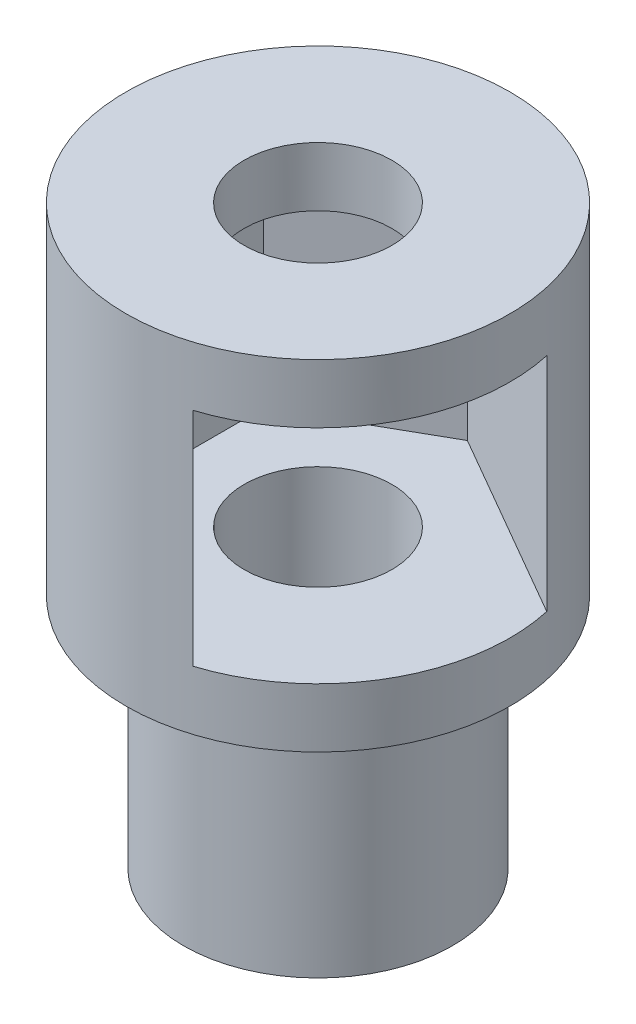
SolidWorks part; units mm, degrees
ref_plane "Front Plane" through (0, 0, 0) normal (0, 0, 1) x (1, 0, 0)
ref_plane "Top Plane" through (0, 0, 0) normal (0, 1, 0) x (1, 0, 0)
ref_plane "Right Plane" through (0, 0, 0) normal (1, 0, 0) x (0, 0, -1)
sketch "Sketch1" plane through (0, 0, 0) normal (0, 1, 0) x (1, 0, 0)
  circle A0 centre (0, 0) radius 4.55
  dimension "D1" = 9.1
extrude "Boss-Extrude1" add sketch "Sketch1" along normal blind 8 contours A0
sketch "Sketch2" plane through (0, 8, 0) normal (0, 1, 0) x (1, 0, 0)
  circle A0 centre (0, 0) radius 2.5
extrude "Cut-Extrude1" cut sketch "Sketch2" against normal blind 8
sketch "Sketch3" plane through (0, 8, 0) normal (0, 1, 0) x (1, 0, 0)
  circle A0 centre (0, 0) radius 6.5
  dimension "D1" = 13
extrude "Boss-Extrude4" add sketch "Sketch3" along normal blind 9.5 contours A0
sketch "Sketch5" plane through (0, 17.5, 0) normal (0, 1, 0) x (1, 0, 0)
  line L0 (0, 0) -> (4.3938, 0) construction
  line L3 (4.3938, 2.521) -> (4.3938, -2.521) construction
  line L5 (4.3938, -2.521) -> (-0.0062, -5.0614) construction
  line L9 (-0.0062, -5.0614) -> (-4.4062, -2.521) construction
  line L12 (-4.4062, -2.521) -> (-4.4062, 2.5597)
  line L13 (-4.4062, 2.5597) -> (-0.0062, 5.0614)
  line L14 (-0.0062, 5.0614) -> (4.3938, 2.521) construction
  line L15 (-4.1854, -2.6484) -> (43297.0847, -25002.6484) construction
  line L16 (0.0916, 5.0049) -> (43301.3618, -24994.9951) construction
  line L17 (7.8193, 0.5434) -> (3.436, -7.0487)
  line L18 (-0.0062, 5.0614) -> (7.8193, 0.5434)
  line L19 (3.436, -7.0487) -> (-4.4062, -2.521)
  circle A0 centre (0, 0) radius 6.5 construction
  point P6 (4.3938, 0)
  dimension "D1" = 120
extrude "Cut-Extrude2" cut sketch "Sketch5" against normal blind 7.5
sketch "Sketch6" plane through (0, 17.5, 0) normal (0, 1, 0) x (1, 0, 0)
  circle A0 centre (0, 0) radius 6.5
  dimension "D1" = 13
extrude "Boss-Extrude5" add sketch "Sketch6" along normal blind 2
sketch "Sketch7" plane through (0, 0, 0) normal (0, -1, 0) x (1, 0, 0)
  circle A0 centre (0, 0) radius 2.5
extrude "Cut-Extrude3" cut sketch "Sketch7" against normal through all
